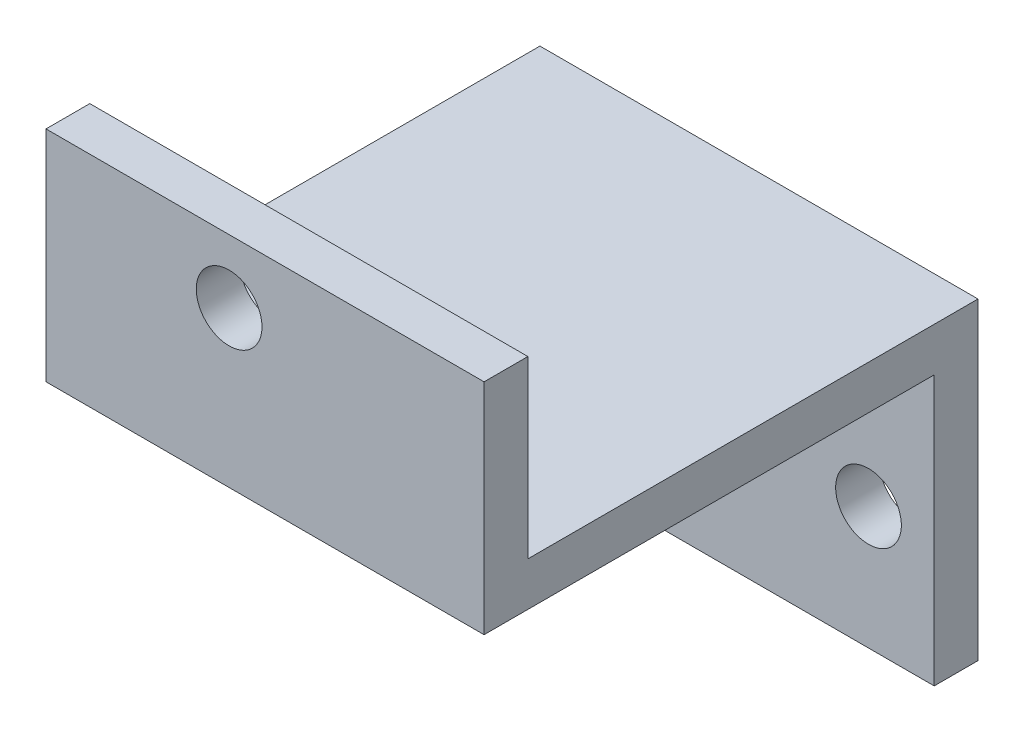
SolidWorks part; units mm, degrees
ref_plane "Front" through (0, 0, 0) normal (0, 0, 1) x (1, 0, 0)
ref_plane "Top" through (0, 0, 0) normal (0, 1, 0) x (1, 0, 0)
ref_plane "Right" through (0, 0, 0) normal (1, 0, 0) x (0, 0, -1)
sketch "Esquisse1" plane through (0, 0, 0) normal (0, 0, 1) x (1, 0, 0)
  line L1 (0, 0) -> (20, 0)
  line L2 (0, 0) -> (0, 14.3)
  line L3 (0, 14.3) -> (20, 14.3)
  line L4 (20, 0) -> (20, 14.3)
  dimension "D1" = 20
  dimension "D2" = 14.3
extrude "Boss.-Extru.1" add sketch "Esquisse1" along normal blind 2
sketch "Esquisse2" plane through (0, 0, 2) normal (0, 0, 1) x (1, 0, 0)
  line L0 (20, 0) -> (20, 14.3) construction
  line L1 (0, 14.3) -> (20, 14.3)
  line L2 (0, 14.3) -> (0, 12.3)
  line L3 (0, 12.3) -> (20, 12.3)
  line L4 (20, 14.3) -> (20, 12.3)
  dimension "D1" = 2
extrude "Boss.-Extru.2" add sketch "Esquisse2" along normal blind 20.55
sketch "Esquisse3" plane through (0, 14.3, 0) normal (0, 1, 0) x (1, 0, 0)
  line L0 (0, -22.55) -> (0, 0) construction
  line L1 (20, -22.55) -> (0, -22.55)
  line L2 (20, -22.55) -> (20, -20.55)
  line L3 (20, -20.55) -> (0, -20.55)
  line L4 (0, -22.55) -> (0, -20.55)
  dimension "D1" = 2
extrude "Boss.-Extru.3" add sketch "Esquisse3" along normal blind 8
sketch "Esquisse4" plane through (0, 0, 0) normal (0, 0, -1) x (-1, 0, 0)
  line L0 (-20, 0) -> (-20, 14.3) construction
  line L1 (0, 14.3) -> (0, 0) construction
  line L3 (0, 0) -> (-20, 0) construction
  circle A0 centre (-17, 5.6) radius 1.5
  circle A1 centre (-3, 5.6) radius 1.5
  dimension "D1" = 3
  dimension "D2" = 3
  dimension "D3" = 3
  dimension "D4" = 3
  dimension "D5" = 5.6
  dimension "D6" = 5.6
extrude "Enlèv. mat.-Extru.2" cut sketch "Esquisse4" against normal blind 8
sketch "Esquisse5" plane through (0, 0, 22.55) normal (0, 0, 1) x (1, 0, 0)
  line L0 (0, 12.3) -> (20, 12.3) construction
  line L2 (0, 22.3) -> (0, 12.3) construction
  circle A0 centre (8.36, 19.4) radius 1.5
  dimension "D1" = 3
  dimension "D2" = 7.1
  dimension "D3" = 8.36
extrude "Enlèv. mat.-Extru.3" cut sketch "Esquisse5" against normal blind 8
